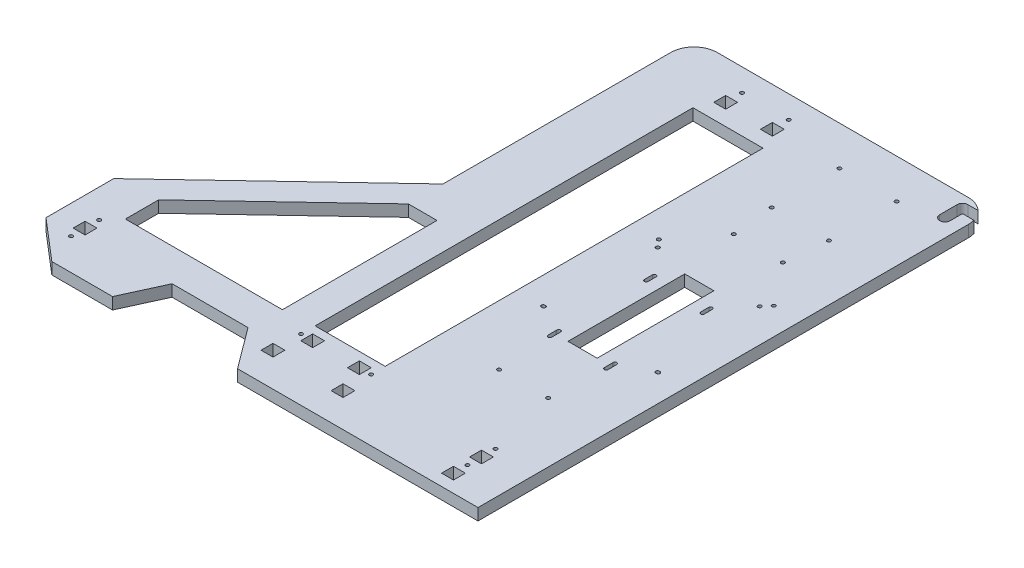
SolidWorks part; units mm, degrees
ref_plane "Front Plane" through (0, 0, 0) normal (0, 0, 1) x (1, 0, 0)
ref_plane "Top Plane" through (0, 0, 0) normal (0, 1, 0) x (1, 0, 0)
ref_plane "Right Plane" through (0, 0, 0) normal (1, 0, 0) x (0, 0, -1)
sketch "Sketch1" plane through (0, 0, 0) normal (0, 1, 0) x (1, 0, 0)
  line L0 (0, 0) -> (-235, 0)
  line L1 (-235, 0) -> (-235, -215)
  line L2 (-235, -215) -> (-380, -352)
  line L3 (-380, -352) -> (-380, -410)
  line L4 (-380, -410) -> (-345, -440)
  line L5 (-345, -440) -> (-293, -440)
  line L6 (-293, -440) -> (-277, -405)
  line L7 (-277, -405) -> (-212, -405)
  line L8 (-212, -405) -> (-185.9255, -440)
  line L9 (-185.9255, -440) -> (0, -440)
  line L10 (0, 0) -> (0, -440)
  line L12 (-293, -440) -> (-185.9255, -440) construction
  dimension "D3" = 235
  dimension "D5" = 58
  dimension "D13" = 190
  dimension "D7" = 35
  dimension "D2" = 126.686
  dimension "D11" = 65
  dimension "D15" = 52
  dimension "D12" = 30
  dimension "D10" = 35
  dimension "D14" = 16
  dimension "D6" = 380
  dimension "D4" = 440
extrude "Boss-Extrude1" add sketch "Sketch1" along normal blind 10
sketch "Sketch16" plane through (0, 10, 0) normal (0, 1, 0) x (1, 0, 0)
  line L0 (0, -440) -> (20, -440)
  line L1 (20, -440) -> (20, 0)
  line L2 (20, 0) -> (0, 0)
  line L3 (0, 0) -> (0, -440)
  dimension "D1" = 20
  dimension "D2" = 90
extrude "Boss-Extrude2" add sketch "Sketch16" against normal through all
sketch "Sketch2" plane through (0, 10, 0) normal (0, 1, 0) x (1, 0, 0)
  line L0 (-235, -215) -> (-235, -405) construction
  line L1 (-277, -405) -> (-212, -405) construction
  line L2 (-345, -440) -> (-345, -318.931) construction
  line L3 (-235, -215) -> (-380, -352) construction
  line L4 (-345, -348.5097) -> (-235, -244.5787)
  line L5 (-235, -244.5787) -> (-210.5, -244.5787)
  line L6 (-210.5, -244.5787) -> (-210.5, -377)
  line L7 (-210.5, -377) -> (-345, -377)
  line L8 (-345, -377) -> (-345, -348.5097)
  line L9 (0, -440) -> (0, 0) construction
  line L10 (-184.5, -375) -> (-124.5, -375)
  line L11 (-184.5, -375) -> (-184.5, -51.35)
  line L12 (-184.5, -51.35) -> (-124.5, -51.35)
  line L13 (-124.5, -375) -> (-124.5, -51.35)
  line L14 (-124.5, -387.1) -> (-184.5, -387.1) construction
  line L15 (-16, -440) -> (-16, 0) construction
  line L16 (20, 0) -> (-235, 0) construction
  line L17 (-355.55, -430.9571) -> (-355.55, -328.899) construction
  line L18 (-21.1, -430.1) -> (-10.9, -430.1)
  line L19 (-21.1, -430.1) -> (-21.1, -419.9)
  line L20 (-21.1, -419.9) -> (-10.9, -419.9)
  line L21 (-10.9, -430.1) -> (-10.9, -419.9)
  line L22 (-21.1, -430.1) -> (-10.9, -419.9) construction
  line L23 (-21.1, -419.9) -> (-10.9, -430.1) construction
  line L24 (-21.1, -406.1) -> (-10.9, -406.1)
  line L25 (-21.1, -406.1) -> (-21.1, -395.9)
  line L26 (-21.1, -395.9) -> (-10.9, -395.9)
  line L27 (-10.9, -406.1) -> (-10.9, -395.9)
  line L28 (-21.1, -406.1) -> (-10.9, -395.9) construction
  line L29 (-21.1, -395.9) -> (-10.9, -406.1) construction
  line L30 (-380, -410) -> (-345, -440) construction
  line L32 (-350.45, -395.9) -> (-360.65, -395.9)
  line L33 (-350.45, -395.9) -> (-350.45, -406.1)
  line L34 (-350.45, -406.1) -> (-360.65, -406.1)
  line L35 (-360.65, -395.9) -> (-360.65, -406.1)
  line L36 (-350.45, -395.9) -> (-360.65, -406.1) construction
  line L37 (-350.45, -406.1) -> (-360.65, -395.9) construction
  line L38 (-185.9255, -440) -> (20, -440) construction
  line L39 (-185.9255, -440) -> (20, -440) construction
  line L40 (-173.924, -33.35) -> (-113.924, -33.35) construction
  line L41 (-154.5, -51.35) -> (-154.5, -33.35) construction
  line L42 (-179.6, -28.25) -> (-169.4, -28.25)
  line L43 (-179.6, -28.25) -> (-179.6, -38.45)
  line L44 (-179.6, -38.45) -> (-169.4, -38.45)
  line L45 (-169.4, -28.25) -> (-169.4, -38.45)
  line L46 (-179.6, -28.25) -> (-169.4, -38.45) construction
  line L47 (-179.6, -38.45) -> (-169.4, -28.25) construction
  line L48 (-129.4, -38.45) -> (-139.6, -28.25) construction
  line L49 (-129.4, -28.25) -> (-139.6, -38.45) construction
  line L50 (-139.6, -28.25) -> (-139.6, -38.45)
  line L51 (-129.4, -38.45) -> (-139.6, -38.45)
  line L52 (-129.4, -28.25) -> (-129.4, -38.45)
  line L53 (-129.4, -28.25) -> (-139.6, -28.25)
  line L54 (-174.5, -33.35) -> (-174.5, -19.35) construction
  line L55 (-134.5, -33.35) -> (-134.5, -19.35) construction
  line L56 (-154.5, -375) -> (-154.5, -440) construction
  line L57 (-174.5, -387.1) -> (-134.5, -387.1) construction
  line L58 (-129.4, -392.2) -> (-139.6, -382) construction
  line L59 (-179.6, -382) -> (-169.4, -382)
  line L60 (-179.6, -382) -> (-179.6, -392.2)
  line L61 (-179.6, -392.2) -> (-169.4, -392.2)
  line L62 (-169.4, -382) -> (-169.4, -392.2)
  line L63 (-179.6, -382) -> (-169.4, -392.2) construction
  line L64 (-179.6, -392.2) -> (-169.4, -382) construction
  line L65 (-129.4, -382) -> (-139.6, -392.2) construction
  line L66 (-139.6, -382) -> (-139.6, -392.2)
  line L67 (-129.4, -392.2) -> (-139.6, -392.2)
  line L68 (-129.4, -382) -> (-129.4, -392.2)
  line L69 (-129.4, -382) -> (-139.6, -382)
  line L70 (-119.4, -416.2) -> (-129.6, -406) construction
  line L71 (-189.6, -406) -> (-179.4, -406)
  line L72 (-189.6, -406) -> (-189.6, -416.2)
  line L73 (-189.6, -416.2) -> (-179.4, -416.2)
  line L74 (-179.4, -406) -> (-179.4, -416.2)
  line L75 (-189.6, -406) -> (-179.4, -416.2) construction
  line L76 (-189.6, -416.2) -> (-179.4, -406) construction
  line L77 (-119.4, -406) -> (-129.6, -416.2) construction
  line L78 (-129.6, -406) -> (-129.6, -416.2)
  line L79 (-119.4, -416.2) -> (-129.6, -416.2)
  line L80 (-119.4, -406) -> (-119.4, -416.2)
  line L81 (-119.4, -406) -> (-129.6, -406)
  line L82 (-360.65, -395.9) -> (-10.9, -395.9) construction
  circle A0 centre (-16, -413) radius 1.55
  circle A1 centre (-16, -389) radius 1.55
  circle A2 centre (-355.55, -413) radius 1.55
  circle A3 centre (-355.55, -389) radius 1.55
  circle A4 centre (-174.5, -19.35) radius 1.55
  circle A5 centre (-134.5, -19.35) radius 1.55
  circle A6 centre (-124.5, -387.1) radius 1.55
  circle A7 centre (-184.5, -387.1) radius 1.55
  point P25 (-16, -425)
  point P30 (-16, -401)
  point P44 (-355.55, -401)
  point P61 (-174.5, -33.35)
  point P72 (-134.5, -33.35)
  point P85 (-174.5, -387.1)
  point P94 (-134.5, -387.1)
  point P95 (-184.5, -411.1)
  point P104 (-124.5, -411.1)
  point P105 (-154.5, -387.1)
  dimension "D13" = 3.1
  dimension "D14" = 3.1
  dimension "D23" = 3.1
  dimension "D24" = 3.1
  dimension "D31" = 3.1
  dimension "D37" = 3.1
  dimension "D1" = 21.5
  dimension "D2" = 28
  dimension "D3" = 24.5
  dimension "D4" = 60
  dimension "D7" = 26
  dimension "D8" = 10.2
  dimension "D9" = 10.2
  dimension "D10" = 10.2
  dimension "D11" = 10.2
  dimension "D12" = 24
  dimension "D15" = 24
  dimension "D19" = 10.2
  dimension "D20" = 10.2
  dimension "D26" = 12
  dimension "D27" = 10.2
  dimension "D28" = 10.2
  dimension "D33" = 10.2
  dimension "D38" = 10.2
  dimension "D39" = 10.2
  dimension "D41" = 24
  dimension "D34" = 30
  dimension "D36" = 12.1
  dimension "D30" = 18
  dimension "D29" = 40
  dimension "D17" = 15
  dimension "D32" = 14
  dimension "D35" = 20
  dimension "D16" = 12
  dimension "D21" = 90
  dimension "D25" = 24
  dimension "D5" = 353.75
  dimension "D22" = 349.75
  dimension "D40" = 30
  dimension "D6" = 65
  dimension "D42" = 0
  dimension "D43" = 0
  dimension "D18" = 16
extrude "Cut-Extrude1" cut sketch "Sketch2" against normal through all
fillet "Fillet1" radius 20 2 edges at (-235, 5, 0) (20, 5, 0)
sketch "Sketch11" [suppressed] plane through (0, 10, 0) normal (0, 1, 0) x (1, 0, 0)
  line L0 (-124.5, -213.175) -> (20, -213.175) construction
  line L1 (20, -440) -> (20, -20) construction
  line L3 (-52.25, -213.175) -> (-52.25, -440) construction
  line L6 (-124.5, -375) -> (-124.5, -51.35) construction
  line L8 (-185.9255, -440) -> (20, -440) construction
  circle A0 centre (-52.25, -413) radius 12.5
  circle A1 centre (-16, -413) radius 1.55 construction
  dimension "D1" = 25
  dimension "D2" = 0
  dimension "D3" = 0
extrude "WiringHole" [suppressed] cut sketch "Sketch11" against normal through all
sketch "Sketch9" [suppressed] plane through (0, 10, 0) normal (0, 1, 0) x (1, 0, 0)
  line L0 (-52.25, -400.5) -> (-52.25, 0) construction
  line L1 (0, 0) -> (-215, 0) construction
  line L2 (-124.5, -213.175) -> (20, -213.175) construction
  line L3 (-124.5, -375) -> (-124.5, -51.35) construction
  line L4 (-4.75, -124.675) -> (-4.75, -301.675) construction
  line L6 (-99.75, -124.675) -> (-4.75, -124.675) construction
  line L7 (-4.75, -301.675) -> (-99.75, -301.675) construction
  line L8 (-99.75, -301.675) -> (-99.75, -124.675) construction
  line L9 (20, -440) -> (20, -20) construction
  circle A0 centre (-52.25, -413) radius 12.5 construction
  circle A1 centre (-99.75, -124.675) radius 1.55
  circle A2 centre (-4.75, -124.675) radius 1.55
  circle A3 centre (-4.75, -301.675) radius 1.55
  circle A4 centre (-99.75, -301.675) radius 1.55
  dimension "D3" = 3.1
  dimension "D4" = 3.1
  dimension "D1" = 95
  dimension "D2" = 177
  dimension "D5" = 47.5
extrude "MountingHoles-PSU" [suppressed] cut sketch "Sketch9" against normal through all
sketch "Sketch10" plane through (0, 10, 0) normal (0, 1, 0) x (1, 0, 0)
  line L0 (-124.5, -213.175) -> (20, -213.175) construction
  line L1 (20, -440) -> (20, -20) construction
  line L2 (-64.75, -228.175) -> (-39.75, -228.175) construction
  line L3 (-52.25, -213.175) -> (-52.25, 0) construction
  line L7 (-124.5, -375) -> (-124.5, -51.35) construction
  line L8 (-64.75, -278.175) -> (-39.75, -278.175)
  line L9 (-64.75, -278.175) -> (-64.75, -178.175)
  line L10 (-64.75, -178.175) -> (-39.75, -178.175)
  line L11 (-39.75, -278.175) -> (-39.75, -178.175)
  line L12 (-64.75, -278.175) -> (-39.75, -178.175) construction
  line L13 (-64.75, -178.175) -> (-39.75, -278.175) construction
  line L15 (0, 0) -> (-215, 0) construction
  line L17 (-52.25, -213.175) -> (-52.25, -440) construction
  line L18 (-185.9255, -440) -> (20, -440) construction
  line L19 (-64.75, -213.175) -> (-39.75, -213.175) construction
  line L20 (-52.25, -278.175) -> (-52.25, -178.175) construction
  dimension "D1" = 25
  dimension "D2" = 100
  dimension "D3" = 0
  dimension "D4" = 0
  dimension "D5" = 0
  dimension "D6" = 15
extrude "WiringSlot" cut sketch "Sketch10" against normal through all
sketch "CenterLines" plane through (0, 10, 0) normal (0, 1, 0) x (1, 0, 0)
  line L0 (-52.25, -278.175) -> (-52.25, -178.175) construction
  line L1 (-64.75, -278.175) -> (-39.75, -278.175) construction
  line L2 (-39.75, -178.175) -> (-64.75, -178.175) construction
  line L3 (-64.75, -228.175) -> (-39.75, -228.175) construction
  line L4 (-64.75, -178.175) -> (-64.75, -278.175) construction
  line L5 (-39.75, -278.175) -> (-39.75, -178.175) construction
ref_plane "Plane1" through (-52.25, 0, 0) normal (1, 0, 0) x (0, 0, -1)
sketch "Sketch6" plane through (0, 10, 0) normal (0, 1, 0) x (1, 0, 0)
  line L0 (-52.25, -278.175) -> (-52.25, -178.175) construction
  line L1 (-76.35, -237.025) -> (-28.15, -237.025) construction
  line L2 (-28.15, -192.575) -> (-28.15, -275.075) construction
  line L3 (-64.75, -278.175) -> (-39.75, -278.175) construction
  line L4 (-64.75, -245.875) -> (-39.75, -245.875) construction
  line L5 (-39.75, -178.175) -> (-64.75, -178.175) construction
  line L6 (-28.15, -192.575) -> (-28.15, -199.575) construction
  line L7 (-26.6, -192.575) -> (-26.6, -199.575)
  line L8 (-29.7, -192.575) -> (-29.7, -199.575)
  line L9 (-64.75, -228.175) -> (-39.75, -228.175) construction
  line L10 (-64.75, -178.175) -> (-64.75, -278.175) construction
  line L11 (-39.75, -278.175) -> (-39.75, -178.175) construction
  line L12 (-28.15, -282.075) -> (-28.15, -275.075) construction
  line L13 (-29.7, -282.075) -> (-29.7, -275.075)
  line L14 (-76.35, -274.475) -> (-76.35, -199.575) construction
  line L15 (-28.15, -282.075) -> (-28.15, -199.575) construction
  line L16 (-26.6, -282.075) -> (-26.6, -275.075)
  arc A2 (-26.6, -192.575) -> (-29.7, -192.575) centre (-28.15, -192.575) ccw
  arc A3 (-29.7, -199.575) -> (-26.6, -199.575) centre (-28.15, -199.575) ccw
  circle A4 centre (-76.35, -274.475) radius 1.55
  circle A6 centre (-76.35, -199.575) radius 1.55
  arc A8 (-29.7, -282.075) -> (-26.6, -282.075) centre (-28.15, -282.075) ccw
  arc A9 (-26.6, -275.075) -> (-29.7, -275.075) centre (-28.15, -275.075) ccw
  point P20 (-28.15, -196.075)
  point P25 (-28.15, -278.575)
  dimension "D8" = 3.1
  dimension "D12" = 3.1
  dimension "D4" = 1.55
  dimension "D5" = 1.55
  dimension "D11" = 82.5
  dimension "D14" = 74.9
  dimension "D2" = 24.1
  dimension "D3" = 48.2
  dimension "D6" = 8.85
  dimension "D9" = 7
  dimension "D10" = 7
extrude "MountingHoles-RAMPS" cut sketch "Sketch6" against normal through all
mirror "Mirror1" about plane through (-52.25, 0, 0) normal (1, 0, 0) of "MountingHoles-RAMPS"
sketch "Sketch5" plane through (0, 10, 0) normal (0, 1, 0) x (1, 0, 0)
  line L0 (-39.75, -228.175) -> (-64.75, -228.175) construction
  line L3 (-39.75, -278.175) -> (-39.75, -178.175) construction
  line L5 (-64.75, -178.175) -> (-64.75, -278.175) construction
  line L7 (-31.25, -127.675) -> (-73.25, -127.675) construction
  line L8 (-31.25, -328.675) -> (-73.25, -328.675) construction
  line L9 (-52.25, -228.175) -> (-52.25, -127.675) construction
  line L10 (-52.25, -228.175) -> (-52.25, -328.675) construction
  circle A0 centre (-73.25, -127.675) radius 1.55
  circle A1 centre (-31.25, -127.675) radius 1.55
  circle A2 centre (-31.25, -328.675) radius 1.55
  circle A3 centre (-73.25, -328.675) radius 1.55
  point P17 (-52.25, -127.675)
  point P22 (-52.25, -328.675)
  dimension "D2" = 3.1
  dimension "D5" = 3.1
  dimension "D6" = 3.1
  dimension "D7" = 3.1
  dimension "D1" = 21
  dimension "D3" = 201
  dimension "D4" = 100.5
  dimension "D8" = 21
  dimension "D9" = 21
  dimension "D10" = 100.5
extrude "MountingHoles-Melzi" cut sketch "Sketch5" against normal through all
sketch "Sketch13" plane through (0, 0, 0) normal (0, -1, 0) x (-1, 0, 0)
  line L0 (64.75, -213.175) -> (124.5, -213.175) construction
  line L1 (124.5, -375) -> (124.5, -51.35) construction
  line L2 (101.46, -262.69) -> (101.46, -163.66) construction
  line L3 (52.25, -278.175) -> (52.25, -178.175) construction
  line L4 (64.75, -178.175) -> (64.75, -278.175) construction
  line L6 (101.46, -262.69) -> (3.56, -262.69) construction
  circle A0 centre (101.46, -163.66) radius 1.55
  circle A1 centre (101.46, -262.69) radius 1.55
  circle A2 centre (8.62, -170.14) radius 1.55
  circle A3 centre (3.56, -262.69) radius 1.55
  point P11 (101.46, -213.175)
  dimension "D8" = 3.1
  dimension "D6" = 3.1
  dimension "D1" = 3.1
  dimension "D2" = 49.515
  dimension "D3" = 49.21
  dimension "D4" = 6.48
  dimension "D5" = 92.84
  dimension "D7" = 97.9
extrude "Mountingholes-Smoothieboard" cut sketch "Sketch13" against normal through all
mirror "Flipped" about plane through (-52.25, 0, 0) normal (1, 0, 0) of "Mountingholes-Smoothieboard"
sketch "Sketch21" plane through (0, 10, 0) normal (0, 1, 0) x (1, 0, 0)
  line L0 (-52.25, -178.175) -> (-52.25, 0) construction
  line L1 (-39.75, -178.175) -> (-64.75, -178.175) construction
  line L2 (0, 0) -> (-215, 0) construction
  line L3 (-52.25, -62.675) -> (-23.3697, -62.675) construction
  circle A0 centre (-27.75, -33.675) radius 1.55
  circle A1 centre (-76.75, -33.675) radius 1.55
  circle A2 centre (-76.75, -91.675) radius 1.55
  circle A3 centre (-27.75, -91.675) radius 1.55
  circle A4 centre (-31.25, -127.675) radius 1.55 construction
  dimension "D1" = 3.1
  dimension "D2" = 24.5
  dimension "D3" = 29
  dimension "D4" = 65
extrude "Pi" cut sketch "Sketch21" against normal through all
sketch "Sketch17" plane through (0, 10, 0) normal (0, 1, 0) x (1, 0, 0)
  line L0 (0, 0) -> (20, 0) construction
  line L1 (20, -23.6361) -> (20, 0) construction
  line L2 (20, -440) -> (20, -20) construction
  line L3 (20, -10) -> (5, -10) construction
  line L4 (20, -14.5) -> (5, -14.5)
  line L5 (20, -5.5) -> (5, -5.5)
  arc A0 (20, -14.5) -> (20, -5.5) centre (20, -10) ccw
  arc A1 (5, -5.5) -> (5, -14.5) centre (5, -10) ccw
  point P8 (12.5, -10)
  dimension "D1" = 9
  dimension "D2" = 15
  dimension "D3" = 10
extrude "Cut-Extrude3" cut sketch "Sketch17" against normal through all
sketch "Sketch18" plane through (0, 10, 0) normal (0, 1, 0) x (1, 0, 0)
  line L0 (5, -5.5) -> (5, -14.5) construction
  line L1 (0.5, -10) -> (5, -10) construction
  line L2 (5, -10) -> (5, -25) construction
  line L3 (9.5, -10) -> (9.5, -25)
  line L4 (0.5, -10) -> (0.5, -25)
  arc A0 (5, -5.5) -> (5, -14.5) centre (5, -10) ccw construction
  arc A1 (9.5, -10) -> (0.5, -10) centre (5, -10) ccw
  arc A2 (0.5, -25) -> (9.5, -25) centre (5, -25) ccw
  point P10 (5, -17.5)
  dimension "D1" = 9
  dimension "D2" = 0
  dimension "D3" = 15
extrude "Cut-Extrude4" cut sketch "Sketch18" against normal through all
sketch "Sketch19" plane through (0, 10, 0) normal (0, 1, 0) x (1, 0, 0)
  line L0 (-5, -25) -> (15, -25) construction
  line L1 (5, -25) -> (5, -5.5) construction
  circle A0 centre (15, -25) radius 1.55
  arc A1 (5, -5.5) -> (0.5, -10) centre (5, -10) ccw construction
  circle A2 centre (-5, -25) radius 1.55
  dimension "D1" = 10
  dimension "D2" = 3.1
extrude "Cut-Extrude5" [suppressed] cut sketch "Sketch19" against normal through all
equation "\"Y-ROD-SPACING\"=75"
equation "\"Y-BED-OFFSET\"=2"
equation "\"Y-BED-ROD-INSET\"=3.5"
equation "\"T-SLOT-NUT-FILLET-RADIUS\"=0.25"
equation "\"T-SLOT-SCREW-SHAFT-RADIUS\"=1.75"
equation "\"T-SLOT-SCREW-SHAFT-CUTOUT-LENGTH\"=10.5"
equation "\"T-SLOT-NUT-DEPTH\"=4.2"
equation "\"T-SLOT-NUT-WIDTH\"=3"
equation "\"T-SLOT-NUT-END-DISTANCE\"=8"
equation "\"ACRYLIC-TAB-CUTOUT-SIZE\"=\"ACRYLIC-THICKNESS\"+\"ACRYLIC-TAB-TOLERANCE\"*2"
equation "\"ACRYLIC-TAB-WIDTH\"=\"ACRYLIC-THICKNESS\""
equation "\"ACRYLIC-M3-HOLE\"=3.1"
equation "\"SMOOTHROD-CAP-SCREW-DISTANCE\"=20"
equation "\"FRAME-WIDTH-INNER\"=370"
equation "\"D24@Sketch2\"=\"ACRYLIC-M3-HOLE\""
equation "\"D23@Sketch2\"=\"ACRYLIC-M3-HOLE\""
equation "\"D19@Sketch2\"=\"ACRYLIC-THICKNESS\"+\"ACRYLIC-TAB-TOLERANCE\"*2"
equation "\"D20@Sketch2\"=\"ACRYLIC-TAB-WIDTH\"+\"ACRYLIC-TAB-TOLERANCE\"*2"
equation "\"D37@Sketch2\"=\"ACRYLIC-M3-HOLE\""
equation "\"D33@Sketch2\"=\"ACRYLIC-TAB-CUTOUT-SIZE\""
equation "\"D38@Sketch2\"=\"ACRYLIC-TAB-CUTOUT-SIZE\""
equation "\"D39@Sketch2\"=\"ACRYLIC-TAB-CUTOUT-SIZE\""
equation "\"D13@Sketch2\"=\"ACRYLIC-M3-HOLE\""
equation "\"D14@Sketch2\"=\"ACRYLIC-M3-HOLE\""
equation "\"D8@Sketch2\"=\"ACRYLIC-TAB-CUTOUT-SIZE\""
equation "\"D9@Sketch2\"=\"ACRYLIC-TAB-CUTOUT-SIZE\""
equation "\"D10@Sketch2\"=\"ACRYLIC-TAB-CUTOUT-SIZE\""
equation "\"D11@Sketch2\"=\"ACRYLIC-TAB-CUTOUT-SIZE\""
equation "\"D31@Sketch2\"=\"ACRYLIC-M3-HOLE\""
equation "\"D27@Sketch2\"=\"ACRYLIC-THICKNESS\"+\"ACRYLIC-TAB-TOLERANCE\"*2"
equation "\"D28@Sketch2\"=\"ACRYLIC-TAB-WIDTH\"+\"ACRYLIC-TAB-TOLERANCE\"*2"
equation "\"NEMA17-HOLE-SPACING\"=31"
equation "\"NEMA17-CENTRAL-CUTOUT\"=22.5"
equation "\"Z-BRACKET-REACH\"=55"
equation "\"TOP-BRACKET-SPACING\"=40"
equation "\"D29@Sketch2\"=\"TOP-BRACKET-SPACING\""
equation "\"ACRYLIC-THICKNESS\"=10"
equation "\"SMOOTHROD-Z-LENGTH\"=350"
equation "\"D5@Sketch2\"=\"SMOOTHROD-Z-LENGTH\"-\"SMOOTHROD-TIGHTENING-HEADROOM\"+4"
equation "\"SMOOTHROD-X-LENGTH\"=350"
equation "\"SMOOTHROD-Y-LENGTH\"=350"
equation "\"D22@Sketch2\"=\"SMOOTHROD-Y-LENGTH\"-\"SMOOTHROD-TIGHTENING-HEADROOM\""
equation "\"SMOOTHROD-TIGHTENING-HEADROOM\"=.25"
equation "\"X-ROD-SPACING\"=45"
equation "\"Z-ROD-SPACING\"=17.5"
equation "\"LEADSCREW-Z-LENGTH\"=300"
equation "\"SCREW-HEAD-RADIUS\"=6"
equation "\"PRINTED-X-SMOOTHROD-DIAMETER\"=8.2"
equation "\"PRINTED-X-SMOOTHROD-CUTOUT\"=10"
equation "\"PRINTED-X-BASE-HEIGHT\"=10"
equation "\"PRINTED-LM8UU-CUTOUT-SIZE\"=15.25"
equation "\"PRINTED-LM8UU-CUTOUT-LENGTH\"=24.5"
equation "\"PRINTED-X-IDLER-HEIGHT\"=16"
equation "\"PSU-MOUNTING-WIDTH\"=95"
equation "\"PSU-MOUNTING-HEIGHT\"=177"
equation "\"D1@Sketch9\"=\"PSU-MOUNTING-WIDTH\""
equation "\"D3@Sketch9\"=\"ACRYLIC-M3-HOLE\""
equation "\"D1@Boss-Extrude1\"=\"ACRYLIC-THICKNESS\""
equation "\"D6@Sketch1\"=\"SMOOTHROD-Y-LENGTH\"+30"
equation "\"D4@Sketch9\"=\"ACRYLIC-M3-HOLE\""
equation "\"D2@Sketch9\"=\"PSU-MOUNTING-HEIGHT\""
equation "\"D5@Sketch9\"=\"PSU-MOUNTING-WIDTH\"/2"
equation "\"D4@Sketch1\"=\"SMOOTHROD-Z-LENGTH\"+90"
equation "\"D8@Sketch6\"=\"ACRYLIC-M3-HOLE\""
equation "\"D12@Sketch6\"=\"ACRYLIC-M3-HOLE\""
equation "\"D2@Sketch5\"=\"ACRYLIC-M3-HOLE\""
equation "\"D5@Sketch5\"=\"ACRYLIC-M3-HOLE\""
equation "\"D6@Sketch5\"=\"ACRYLIC-M3-HOLE\""
equation "\"D7@Sketch5\"=\"ACRYLIC-M3-HOLE\""
equation "\"D1@Sketch13\"=\"ACRYLIC-M3-HOLE\""
equation "\"D6@Sketch13\"=\"ACRYLIC-M3-HOLE\""
equation "\"D8@Sketch13\"=\"ACRYLIC-M3-HOLE\""
equation "\"D4@Sketch6\"=\"ACRYLIC-M3-HOLE\"/2"
equation "\"D5@Sketch6\"=\"ACRYLIC-M3-HOLE\"/2"
equation "\"Y-BED-SCREW-SPACING\"=209"
equation "\"Y-BED-SCREW-CUTOUT-SLOT-HEIGHT\"=2"
equation "\"ACRYLIC-THICKNESS2\"=4.5"
equation "\"ACRYLIC-TAB-TOLERANCE\"=.1"
equation "\"Z-ROD-INSET\"=16"
equation "\"SCREW-LENGTH-FRAME\"=\"ACRYLIC-THICKNESS\" + 10"
equation "\"SCREW-LENGTH-MOTOR\"=\"ACRYLIC-THICKNESS\" + 5"
equation "\"SCREW-LENGTH-EXTRUDER\"=28"
equation "\"Y-BELT-TO-ROD-DISTANCE\"=20"
equation "\"SPOOL-HOLDER-ROD-SPACING\"=150"
equation "\"ACRYLIC-X-CARRIAGE-WIDTH\"=55"
equation "\"ACRYLIC-X-CARRIAGE-HEIGHT\"=75"
equation "\"ACRYLIC-X-CARRIAGE-LM8UU-CUTOUT-WIDTH\"=24.25"
equation "\"ACRYLIC-X-CARRIAGE-SCREW-SPACING-X\"=15"
equation "\"ACRYLIC-X-CARRIAGE-SCREW-SPACING-Y\"=33"
equation "\"ACRYLIC-X-CARRIAGE-CENTER-TAB-SPACING\"=14"
equation "\"ACRYLIC-X-CARRIAGE-EXTRUDER-OFFSET\"=26"
equation "\"ACRYLIC-X-CARRIAGE-EXTRUDER-ANGLE\"=90"
equation "\"ACRYLIC-X-CARRIAGE-EXTRUDER-SHELF-DEPTH\"=\"ACRYLIC-X-CARRIAGE-EXTRUDER-OFFSET\" + 28"
equation "\"ACRYLIC-X-CARRIAGE-EXTRUDER-BRACE-SPACING\"=23"
equation "\"ACRYLIC-X-CARRIAGE-EXTRUDER-BRACE-TAB-OFFSET\"=20"
equation "\"ACRYLIC-X-CARRIAGE-EXTRUDER-BRACE-HEIGHT\"=35"
equation "\"ACRYLIC-X-CARRIAGE-EXTRUDER-BRACE-SCREW-SPACING\"=22"
equation "\"D1@Sketch19\"=\"SMOOTHROD-CAP-SCREW-DISTANCE\"/2"
equation "\"D2@Sketch19\"=\"ACRYLIC-M3-HOLE\""
equation "\"D1@Sketch21\"=\"ACRYLIC-M3-HOLE\""
